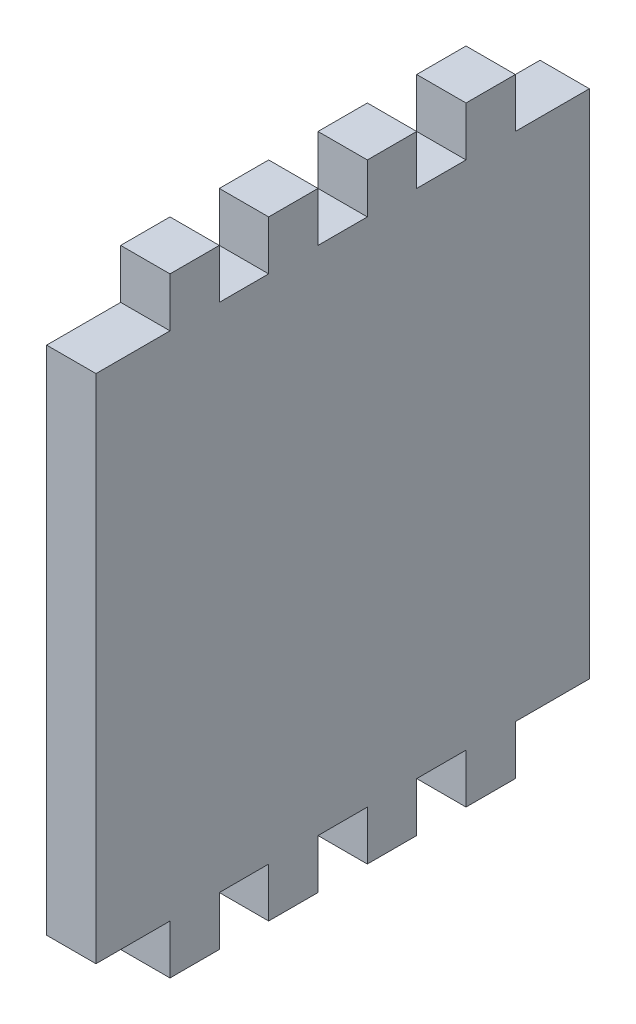
SolidWorks part; units mm, degrees
ref_plane "Front Plane" through (0, 0, 0) normal (0, 0, 1) x (1, 0, 0)
ref_plane "Top Plane" through (0, 0, 0) normal (0, 1, 0) x (1, 0, 0)
ref_plane "Right Plane" through (0, 0, 0) normal (1, 0, 0) x (0, 0, -1)
sketch "Sketch1" plane through (0, 0, 0) normal (1, 0, 0) x (0, 0, -1)
  line L1 (-20.2237, 14.0844) -> (30.5763, 14.0844)
  line L2 (-20.2237, 14.0844) -> (-20.2237, -38.5419)
  line L3 (-20.2237, -38.5419) -> (30.5763, -38.5419)
  line L4 (30.5763, 14.0844) -> (30.5763, -38.5419)
  dimension "D1" = 50.8
  dimension "D2" = 52.6263
extrude "Boss-Extrude1" add sketch "Sketch1" along normal blind 5.08
sketch "Sketch2" plane through (5.08, 0, 0) normal (1, 0, 0) x (0, 0, -1)
  line L0 (5.1763, 14.0844) -> (5.1763, -38.5419) construction
  line L1 (30.5763, 14.0844) -> (-20.2237, 14.0844) construction
  line L2 (-20.2237, -38.5419) -> (30.5763, -38.5419) construction
  line L3 (-20.2237, -12.2288) -> (30.5763, -12.2288) construction
  line L4 (-20.2237, 14.0844) -> (-20.2237, -38.5419) construction
  line L5 (30.5763, -38.5419) -> (30.5763, 14.0844) construction
  line L6 (-12.6037, 14.0844) -> (-12.6037, 19.1644)
  line L7 (7.7163, 14.0844) -> (12.7963, 14.0844)
  line L8 (7.7163, 14.0844) -> (7.7163, 19.1644)
  line L9 (7.7163, 19.1644) -> (12.7963, 19.1644)
  line L10 (12.7963, 14.0844) -> (12.7963, 19.1644)
  line L11 (17.8763, 14.0844) -> (22.9563, 14.0844)
  line L12 (17.8763, 14.0844) -> (17.8763, 19.1644)
  line L13 (17.8763, 19.1644) -> (22.9563, 19.1644)
  line L14 (22.9563, 14.0844) -> (22.9563, 19.1644)
  line L15 (-7.5237, 19.1644) -> (-12.6037, 19.1644)
  line L16 (-7.5237, 14.0844) -> (-7.5237, 19.1644)
  line L17 (-7.5237, 14.0844) -> (-12.6037, 14.0844)
  line L18 (-2.4437, 14.0844) -> (-2.4437, 19.1644)
  line L19 (2.6363, 19.1644) -> (-2.4437, 19.1644)
  line L20 (2.6363, 14.0844) -> (2.6363, 19.1644)
  line L21 (2.6363, 14.0844) -> (-2.4437, 14.0844)
  line L22 (2.6363, -38.5419) -> (-2.4437, -38.5419)
  line L23 (2.6363, -38.5419) -> (2.6363, -43.6219)
  line L24 (2.6363, -43.6219) -> (-2.4437, -43.6219)
  line L25 (-2.4437, -38.5419) -> (-2.4437, -43.6219)
  line L26 (-7.5237, -38.5419) -> (-12.6037, -38.5419)
  line L27 (-7.5237, -38.5419) -> (-7.5237, -43.6219)
  line L28 (-7.5237, -43.6219) -> (-12.6037, -43.6219)
  line L29 (22.9563, -38.5419) -> (22.9563, -43.6219)
  line L30 (17.8763, -43.6219) -> (22.9563, -43.6219)
  line L31 (17.8763, -38.5419) -> (17.8763, -43.6219)
  line L32 (17.8763, -38.5419) -> (22.9563, -38.5419)
  line L33 (12.7963, -38.5419) -> (12.7963, -43.6219)
  line L34 (7.7163, -43.6219) -> (12.7963, -43.6219)
  line L35 (7.7163, -38.5419) -> (7.7163, -43.6219)
  line L36 (7.7163, -38.5419) -> (12.7963, -38.5419)
  line L37 (-12.6037, -38.5419) -> (-12.6037, -43.6219)
  dimension "D1" = 5.08
  dimension "D2" = 5.08
  dimension "D3" = 5.08
  dimension "D4" = 5.08
  dimension "D5" = 2.54
  dimension "D6" = 5.08
extrude "Boss-Extrude2" add sketch "Sketch2" against normal blind 5.08
